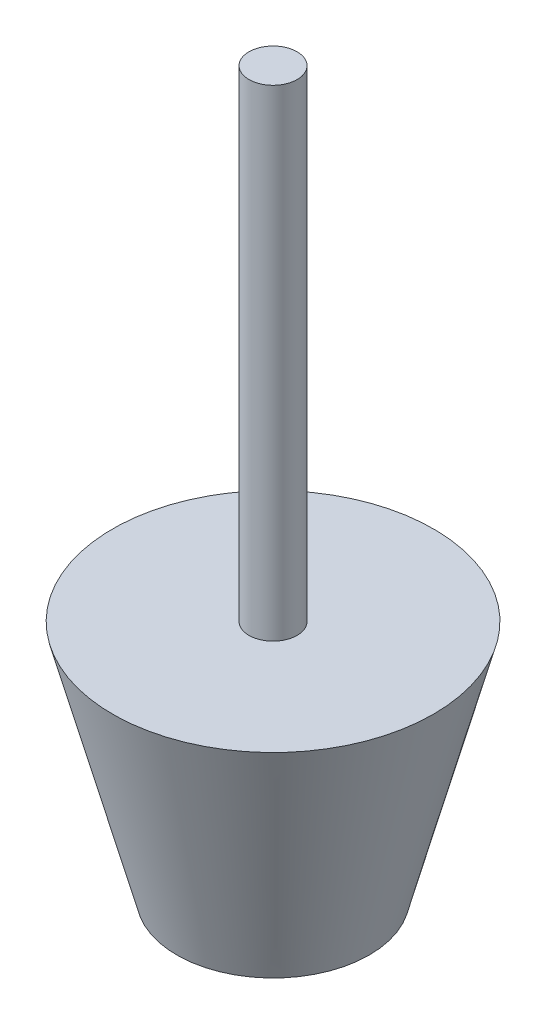
SolidWorks part; units mm, degrees
ref_plane "前基準面" through (0, 0, 0) normal (0, 0, 1) x (1, 0, 0)
ref_plane "上基準面" through (0, 0, 0) normal (0, 1, 0) x (1, 0, 0)
ref_plane "右基準面" through (0, 0, 0) normal (1, 0, 0) x (0, 0, -1)
sketch "草圖1" plane through (0, 0, 0) normal (0, 0, 1) x (1, 0, 0)
  line L0 (-1.5, -15) -> (-10, -15)
  line L1 (-1.5, 15) -> (0, 15)
  line L2 (-1.5, 15) -> (-1.5, -15)
  line L5 (-1.5, 15) -> (1.5, -15) construction
  line L6 (-1.5, -15) -> (1.5, 15) construction
  line L7 (-10, -15) -> (-6, -30)
  line L8 (-6, -30) -> (0, -30)
  line L9 (0, -30) -> (0, -15)
  line L10 (0, -15) -> (0, 15)
  point P0 (0, 0)
  dimension "D1" = 3
  dimension "D2" = 30
  dimension "D3" = 6
  dimension "D4" = 10
  dimension "D5" = 15
revolve "旋轉1" add sketch "草圖1" angle 360 about L9
